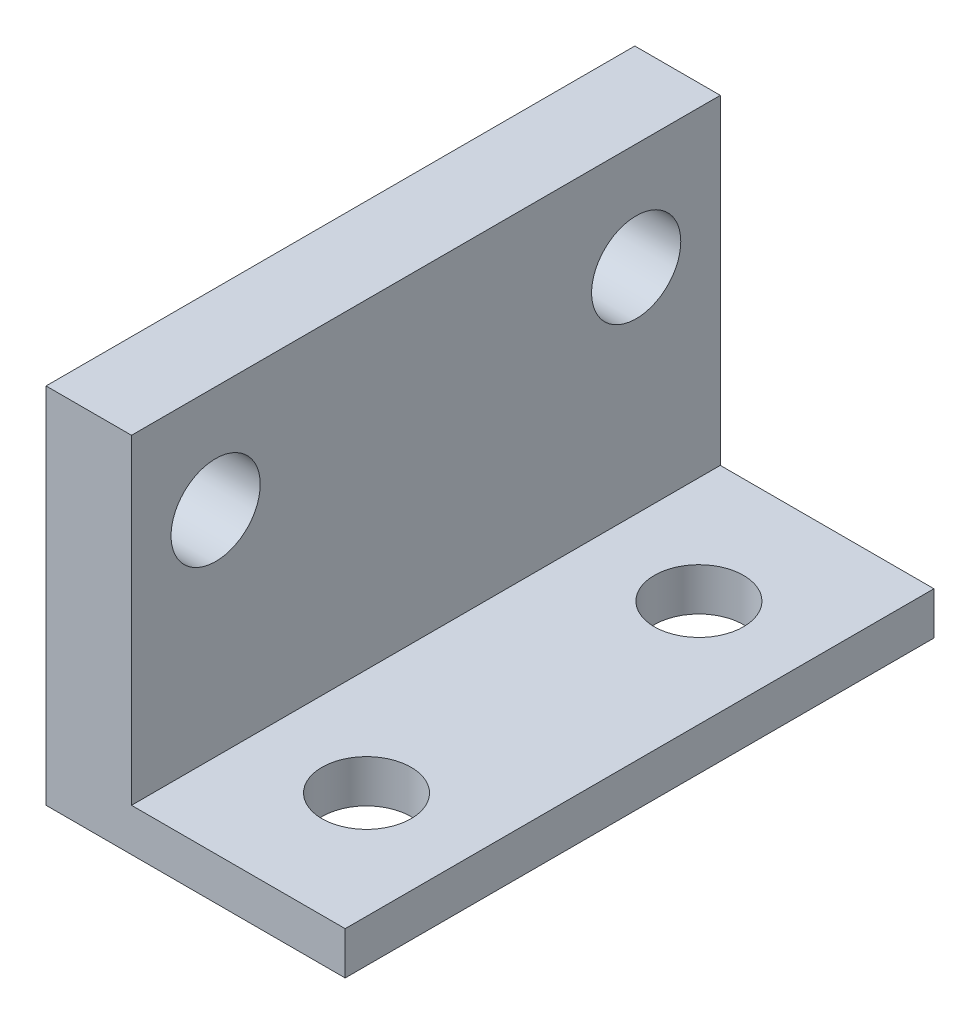
SolidWorks part; units mm, degrees
ref_plane "Front Plane" through (0, 0, 0) normal (0, 0, 1) x (1, 0, 0)
ref_plane "Top Plane" through (0, 0, 0) normal (0, 1, 0) x (1, 0, 0)
ref_plane "Right Plane" through (0, 0, 0) normal (1, 0, 0) x (0, 0, -1)
sketch "Sketch1" plane through (0, 0, 0) normal (0, 0, 1) x (1, 0, 0)
  line L1 (0, 0) -> (17.78, 0)
  line L2 (0, 0) -> (0, 2.54)
  line L3 (0, 2.54) -> (17.78, 2.54)
  line L4 (17.78, 0) -> (17.78, 2.54)
  line L5 (0, 2.54) -> (5.08, 2.54)
  line L6 (0, 2.54) -> (0, 21.59)
  line L7 (0, 21.59) -> (5.08, 21.59)
  line L8 (5.08, 2.54) -> (5.08, 21.59)
  dimension "D1" = 5.08
  dimension "D2" = 12.7
  dimension "D3" = 19.05
  dimension "D4" = 2.54
extrude "Boss-Extrude1" add sketch "Sketch1" along normal blind 35 contours L6 L5 L8 L7 | L2 L1 L4 L3
hole_wizard "Ø5.0mm Dowel Hole1" positions "Sketch2" profile "Sketch3" hole size "Ø5.0" standard "ANSI Metric" end condition through all
sketch "Sketch2" plane through (5.08, 0, 0) normal (1, 0, 0) x (0, 0, -1)
  line L4 (-30, 15.24) -> (-5, 15.24) construction
  line L6 (-35, 0) -> (0, 0) construction
  point P0 (-30, 15.24)
  point P2 (-5, 15.24)
  point P19 (-17.5, 0)
  point P20 (-17.5, 15.24)
  dimension "D1" = 25
  dimension "D2" = 15.24
sketch "Sketch3" plane through (5.08, 15.24, 30) normal (0, 1, 0) x (0, 0, -1)
  line L0 (0, 0) -> (0, 5.08)
  line L1 (0, 5.08) -> (2.65, 5.08)
  line L2 (2.65, 5.08) -> (2.65, 0)
  line L5 (2.65, 0) -> (0, 0)
  line L11 (0, -6.35) -> (0, 107.95) construction
  dimension "Thru Hole Dia." = 5.3
  dimension "Thru Hole Depth" = 5.08
hole_wizard "Ø5.0mm Dowel Hole2" positions "Sketch4" profile "Sketch5" hole size "Ø5.0" standard "ANSI Metric" end condition through all
sketch "Sketch4" plane through (0, 2.54, 0) normal (0, 1, 0) x (1, 0, 0)
  line L0 (5.08, 0) -> (17.78, 0) construction
  line L1 (5.08, -35) -> (17.78, -35) construction
  line L2 (11.43, 0) -> (11.43, -35) construction
  point P0 (11.43, -27.38)
  point P2 (11.43, -7.62)
  dimension "D1" = 7.62
  dimension "D2" = 7.62
sketch "Sketch5" plane through (11.43, 2.54, 27.38) normal (1, 0, 0) x (0, 0, 1)
  line L0 (0, 0) -> (0, 2.54)
  line L1 (0, 2.54) -> (2.65, 2.54)
  line L2 (2.65, 2.54) -> (2.65, 0)
  line L5 (2.65, 0) -> (0, 0)
  line L11 (0, -6.35) -> (0, 107.95) construction
  dimension "Thru Hole Dia." = 5.3
  dimension "Thru Hole Depth" = 2.54
equation "\"wall thicc\"= 2.5mm"
equation "\"press fit\"= 0.3mm"
equation "\"shaft thick\"= 5mm + \"press fit\""
equation "\"D1@Sketch1\"=\"wall thicc\"*2"
equation "\"D4@Sketch1\"=\"wall thicc\""
